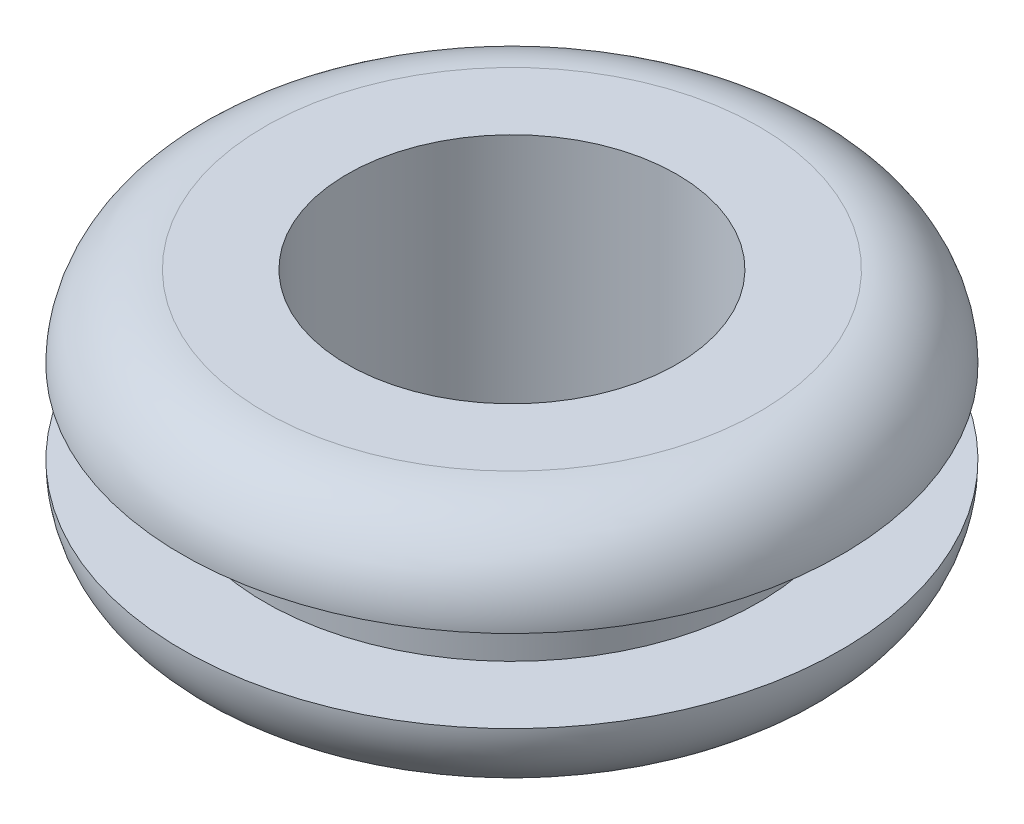
SolidWorks part; units mm, degrees
ref_plane "Front" through (0, 0, 0) normal (0, 0, 1) x (1, 0, 0)
ref_plane "Top" through (0, 0, 0) normal (0, 1, 0) x (1, 0, 0)
ref_plane "Right" through (0, 0, 0) normal (1, 0, 0) x (0, 0, -1)
sketch "Sketch1" plane through (0, 0, 0) normal (1, 0, 0) x (0, 0, -1)
  line L0 (0, -2.3813) -> (0, 2.3813) construction
  line L1 (0, 0.7937) -> (0, -0.7937) construction
  line L2 (-6.35, 2.3813) -> (6.35, 2.3813) construction
  line L3 (-3.175, 0.7937) -> (3.175, 0.7938) construction
  line L4 (-4.7625, 0) -> (4.7625, 0) construction
  point P12 (-3.175, 0.7937)
  point P13 (3.175, 0.7938)
  point P14 (-4.7625, 0)
  point P15 (4.7625, 0)
  point P16 (-6.35, 2.3813)
  point P17 (0, -2.3813)
  point P18 (6.35, 2.3813)
  point P19 (0, 2.3813)
  point P20 (0, 0.7937)
  point P21 (0, -0.7937)
  dimension "Overall Height E" = 4.7625
  dimension "Material Thickness B" = 1.5875
  dimension "Flange Diameter D" = 12.7
  dimension "ID C" = 6.35
  dimension "For ID A" = 9.525
sketch "Sketch2" plane through (0, 0, 0) normal (1, 0, 0) x (0, 0, -1)
  line L0 (-3.175, -2.3813) -> (-3.175, 2.3812)
  line L1 (-3.175, 2.3812) -> (-4.7625, 2.3812)
  line L2 (-4.7625, 0.7937) -> (-4.7625, -0.7937)
  line L3 (-4.7625, 0.7937) -> (-6.35, 0.7937)
  line L4 (-4.7625, -0.7937) -> (-6.35, -0.7937)
  line L5 (-3.175, -2.3813) -> (-4.7625, -2.3813)
  arc A0 (-6.35, 0.7937) -> (-4.7625, 2.3812) centre (-4.7625, 0.7938) cw
  arc A1 (-6.35, -0.7937) -> (-4.7625, -2.3813) centre (-4.7625, -0.7938) ccw
  point P4 (-6.35, 0.7938)
revolve "Revolve1" add sketch "Sketch2" angle 360 about L0
ref_plane "Plane1" through (0, 2.3813, 0) normal (0, -1, 0) x (0, 0, -1)
sketch "Sketch3" plane through (0, 2.3813, 0) normal (0, -1, 0) x (0, 0, -1)
  line L0 (0, -6.35) -> (0, 6.35) construction
  line L1 (-6.35, 0) -> (6.35, 0) construction
  line L2 (0, 3.175) -> (0, -3.175) construction
  line L3 (-3.175, 0) -> (3.175, 0) construction
  line L4 (0, 4.7625) -> (0, -4.7625) construction
  line L5 (-4.7625, 0) -> (4.7625, 0) construction
  point P11 (0, 6.35)
  point P12 (0, 3.175)
  point P13 (0, -3.175)
  point P14 (0, -6.35)
  point P19 (0, -4.7625)
  point P20 (0, 4.7625)
